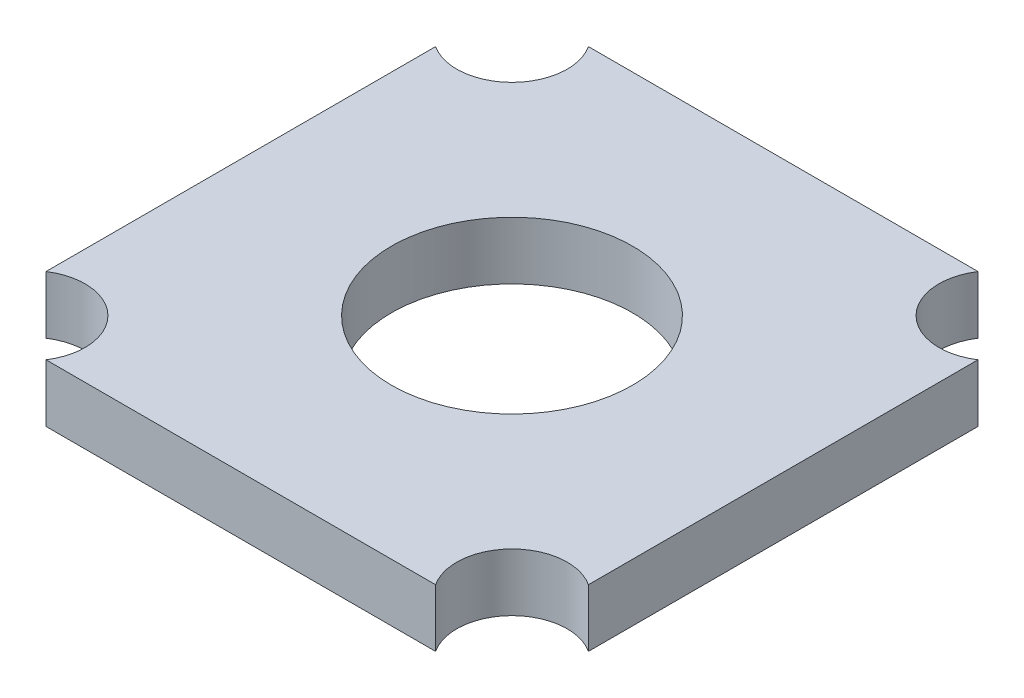
SolidWorks part; units mm, degrees
material "Pine"
ref_plane "Front Plane" through (0, 0, 0) normal (0, 0, 1) x (1, 0, 0)
ref_plane "Top Plane" through (0, 0, 0) normal (0, 1, 0) x (1, 0, 0)
ref_plane "Right Plane" through (0, 0, 0) normal (1, 0, 0) x (0, 0, -1)
sketch "Sketch1" plane through (0, 0, 0) normal (0, 1, 0) x (1, 0, 0)
  line L1 (-85.725, -85.725) -> (85.725, -85.725)
  line L2 (-85.725, -85.725) -> (-85.725, 85.725)
  line L3 (-85.725, 85.725) -> (85.725, 85.725)
  line L4 (85.725, -85.725) -> (85.725, 85.725)
  line L5 (-85.725, -85.725) -> (85.725, 85.725) construction
  line L6 (-85.725, 85.725) -> (85.725, -85.725) construction
  point P0 (0, 0)
  dimension "D1" = 171.45
extrude "Boss-Extrude1" add sketch "Sketch1" along normal blind 18.2562
sketch "Sketch2" plane through (0, 18.2562, 0) normal (0, 1, 0) x (1, 0, 0)
  line L0 (-76.2, -76.2) -> (-76.2, 76.2) construction
  line L1 (-76.2, 76.2) -> (76.2, 76.2) construction
  line L2 (76.2, 76.2) -> (76.2, -76.2) construction
  line L3 (76.2, -76.2) -> (-76.2, -76.2) construction
  line L4 (-76.2, 76.2) -> (76.2, -76.2) construction
  line L5 (-76.2, -76.2) -> (76.2, 76.2) construction
  circle A0 centre (-76.2, 76.2) radius 17.4625
  circle A1 centre (76.2, 76.2) radius 17.4625
  circle A2 centre (76.2, -76.2) radius 17.4625
  circle A3 centre (-76.2, -76.2) radius 17.4625
  dimension "D2" = 34.925
  dimension "D1" = 152.4
extrude "Cut-Extrude1" cut sketch "Sketch2" against normal through all
sketch "Sketch5" plane through (0, 18.2562, 0) normal (0, 1, 0) x (1, 0, 0)
  circle A0 centre (0, 0) radius 38.1
  dimension "D1" = 76.2
extrude "Cut-Extrude2" cut sketch "Sketch5" against normal through all
